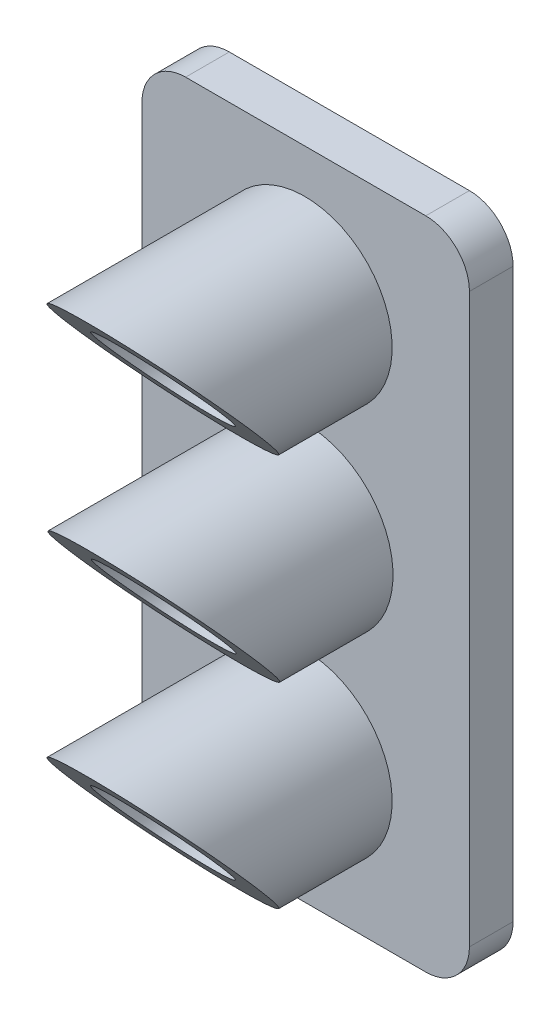
SolidWorks part; units mm, degrees
ref_plane "Front Plane" through (0, 0, 0) normal (0, 0, 1) x (1, 0, 0)
ref_plane "Top Plane" through (0, 0, 0) normal (0, 1, 0) x (1, 0, 0)
ref_plane "Right Plane" through (0, 0, 0) normal (1, 0, 0) x (0, 0, -1)
sketch "Sketch1" plane through (0, 0, 0) normal (0, 0, 1) x (1, 0, 0)
  line L0 (-0.0396, 19.7366) -> (-0.0396, -20.0963) construction
  circle A0 centre (-0.0397, 8.9999) radius 2.5
  circle A1 centre (0, 0) radius 2.5
  circle A2 centre (-0.0396, -8.9999) radius 2.5
  circle A3 centre (-0.0397, 8.9999) radius 4
  circle A4 centre (0, 0) radius 4
  circle A5 centre (-0.0396, -8.9999) radius 4
  dimension "D1" = 9
  dimension "D3" = 8
  dimension "D4" = 8
  dimension "D5" = 8
  dimension "D2" = 9
extrude "Boss-Extrude1" add sketch "Sketch1" along normal blind 10
sketch "Sketch2" plane through (0, 0, 0) normal (0, 0, -1) x (-1, 0, 0)
  line L1 (-7.5, 15) -> (7.5, 15)
  line L2 (-7.5, 15) -> (-7.5, -15)
  line L3 (-7.5, -15) -> (7.5, -15)
  line L4 (7.5, 15) -> (7.5, -15)
  dimension "D1" = 7.5
  dimension "D2" = 7.5
  dimension "D3" = 15
  dimension "D4" = 15
extrude "Boss-Extrude2" add sketch "Sketch2" along normal blind 2
sketch "Sketch3" plane through (0, 0, 0) normal (0, 0, 1) x (1, 0, 0)
  circle A0 centre (-0.0397, 8.9999) radius 2.5
  circle A1 centre (0, 0) radius 2.5
  circle A2 centre (-0.0396, -8.9999) radius 2.5
extrude "Cut-Extrude1" cut sketch "Sketch3" against normal blind 2
sketch "Sketch4" plane through (-7.5, 0, 0) normal (-1, 0, 0) x (0, 0, 1)
  line L0 (10, 4.9999) -> (10, 12.9999) construction
  line L2 (10, 4.0001) -> (10, -3.9999)
  line L3 (10, 13.0001) -> (10, 5.0001)
  line L6 (10, -4.9999) -> (10, -12.9999)
  line L14 (3, 5.0001) -> (3, 4.5727)
  line L15 (3, 4.5727) -> (10, 4.5727)
  line L16 (10, 5.0001) -> (10, 4.5727)
  line L19 (3, -3.9999) -> (10, 4.0001)
  line L20 (3, 5.0001) -> (10, 13.0001)
  line L21 (3, -12.9999) -> (10, -4.9999)
  line L22 (10, -3.9999) -> (10, -4.5108)
  line L23 (10, -4.5108) -> (3, -4.5108)
  line L24 (3, -3.9999) -> (3, -4.5108)
  line L26 (10, -12.9999) -> (10, -13.8314)
  line L27 (10, -13.8314) -> (3, -13.8314)
  line L28 (3, -12.9999) -> (3, -13.8314)
extrude "Cut-Extrude3" cut sketch "Sketch4" against normal blind 22
fillet "Fillet2" radius 2 4 edges at (-7.5, -15, -1) (7.5, -15, -1) (7.5, 15, -1) (-7.5, 15, -1)
